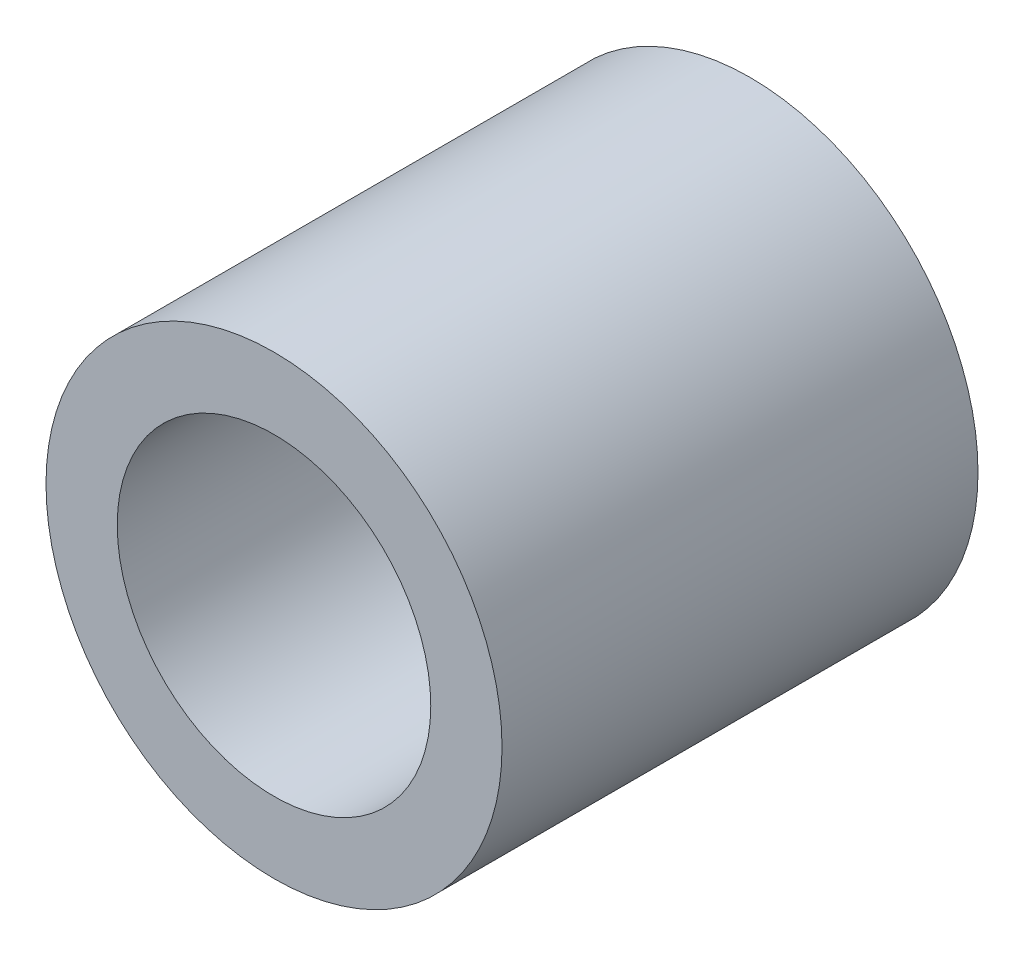
SolidWorks part; units mm, degrees
ref_plane "Alzado" through (0, 0, 0) normal (0, 0, 1) x (1, 0, 0)
ref_plane "Planta" through (0, 0, 0) normal (0, 1, 0) x (1, 0, 0)
ref_plane "Vista lateral" through (0, 0, 0) normal (1, 0, 0) x (0, 0, -1)
sketch "Croquis2" plane through (0, 0, 0) normal (0, 0, 1) x (1, 0, 0)
  circle A0 centre (0, 0) radius 2.75
  circle A1 centre (0, 0) radius 4
extrude "Saliente-Extruir2" add sketch "Croquis2" along normal blind 8.35
